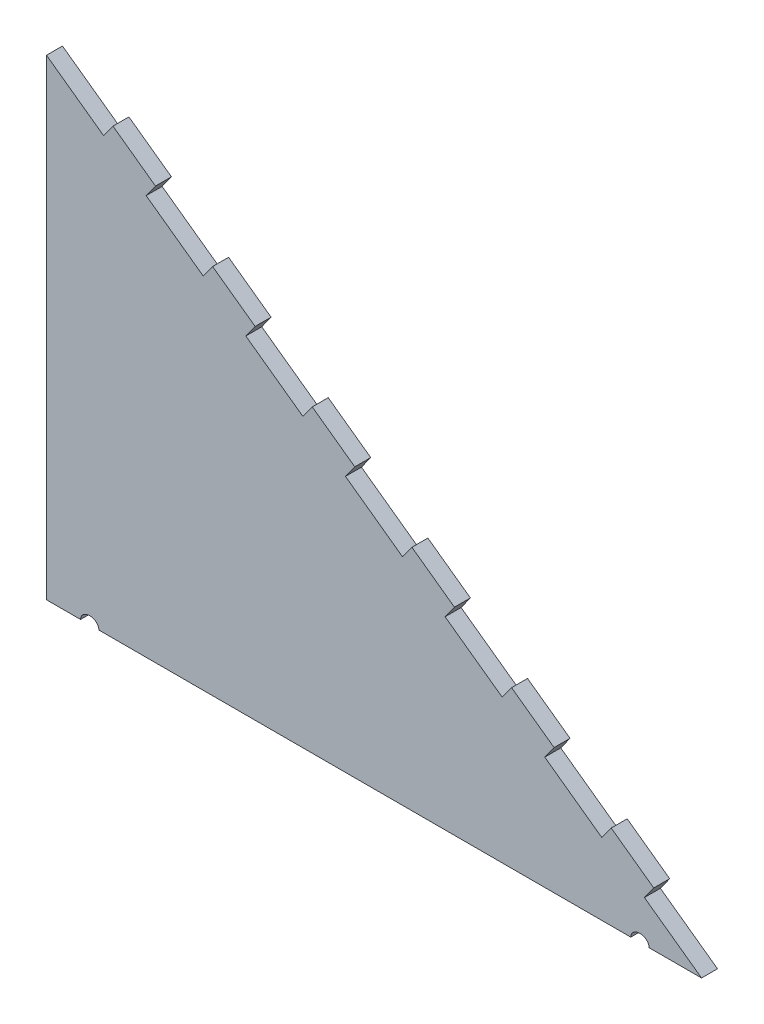
SolidWorks part; units mm, degrees
ref_plane "Front Plane" through (0, 0, 0) normal (0, 0, 1) x (1, 0, 0)
ref_plane "Top Plane" through (0, 0, 0) normal (0, 1, 0) x (1, 0, 0)
ref_plane "Right Plane" through (0, 0, 0) normal (1, 0, 0) x (0, 0, -1)
sketch "Sketch1" plane through (0, 0, 0) normal (0, 0, 1) x (1, 0, 0)
  line L0 (0, 0) -> (13, 0)
  line L1 (250, 0) -> (228.1977, 15.6976)
  line L2 (0, 180) -> (0, 0)
  line L3 (21.8023, 164.3024) -> (25.3642, 169.2495)
  line L4 (25.3642, 169.2495) -> (41.5949, 157.5634)
  line L5 (41.5949, 157.5634) -> (38.033, 152.6163)
  line L6 (59.8352, 136.9186) -> (63.3971, 141.8658)
  line L7 (63.3971, 141.8658) -> (79.6278, 130.1797)
  line L8 (79.6278, 130.1797) -> (76.0659, 125.2325)
  line L9 (97.8682, 109.5349) -> (101.4301, 114.482)
  line L10 (101.4301, 114.482) -> (117.6608, 102.7959)
  line L11 (117.6608, 102.7959) -> (114.0989, 97.8488)
  line L12 (135.9011, 82.1512) -> (139.4631, 87.0983)
  line L13 (139.4631, 87.0983) -> (155.6937, 75.4122)
  line L14 (155.6937, 75.4122) -> (152.1318, 70.4651)
  line L15 (173.9341, 54.7675) -> (177.496, 59.7146)
  line L16 (177.496, 59.7146) -> (193.7267, 48.0285)
  line L17 (193.7267, 48.0285) -> (190.1648, 43.0814)
  line L18 (211.967, 27.3837) -> (215.529, 32.3308)
  line L19 (215.529, 32.3308) -> (231.7597, 20.6447)
  line L20 (231.7597, 20.6447) -> (228.1977, 15.6976)
  line L21 (21.8023, 164.3024) -> (0, 180)
  line L22 (59.8352, 136.9186) -> (38.033, 152.6163)
  line L23 (97.8682, 109.5349) -> (76.0659, 125.2325)
  line L24 (135.9011, 82.1512) -> (114.0989, 97.8488)
  line L25 (173.9341, 54.7675) -> (152.1318, 70.4651)
  line L26 (211.967, 27.3837) -> (190.1648, 43.0814)
  line L27 (20, 0) -> (223, 0)
  line L28 (230, 0) -> (250, 0)
  ellipse E0 centre (226.5, 0) end of major axis (223, 0) minor radius 3 (230, 0) -> (223, 0) ccw
  ellipse E1 centre (16.5, 0) end of major axis (13, 0) minor radius 3 (20, 0) -> (13, 0) ccw
  dimension "D5" = 3
  dimension "D6" = 7
  dimension "D1" = 20
  dimension "D2" = 180
  dimension "D3" = 6.096
  dimension "D4" = 250
  dimension "D7" = 20
  dimension "D8" = 3
  dimension "D9" = 7
  dimension "D10" = 203
extrude "Boss-Extrude1" add sketch "Sketch1" along normal blind 6.096
